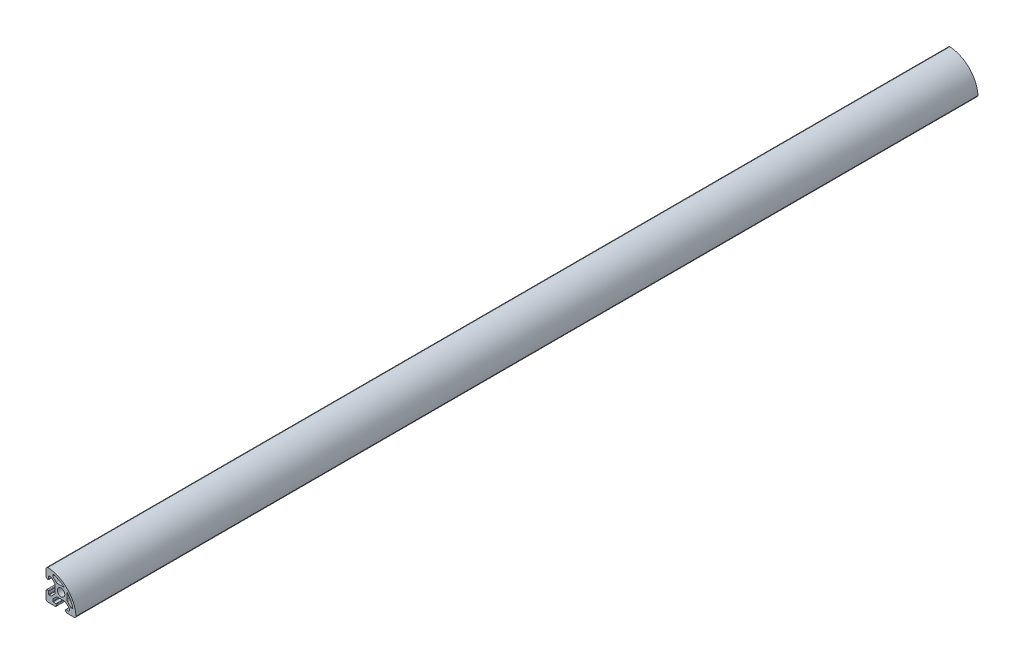
SolidWorks part; units mm, degrees
ref_plane "前视基准面" through (0, 0, 0) normal (0, 0, 1) x (1, 0, 0)
ref_plane "上视基准面" through (0, 0, 0) normal (0, 1, 0) x (1, 0, 0)
ref_plane "右视基准面" through (0, 0, 0) normal (1, 0, 0) x (0, 0, -1)
sketch "草图1" plane through (0, 0, 0) normal (0, 0, 1) x (1, 0, 0)
  line L14 (2.0848, 3.8649) -> (-2.342, 3.8649)
  line L15 (-3.4027, 4.3042) -> (-5.6233, 6.5249)
  line L16 (-5.6233, 6.5249) -> (-5.6233, 7.8649)
  line L22 (-10.1233, 8.4649) -> (-10.1233, 3.5649)
  line L23 (-10.1233, 3.5649) -> (-9.8233, 3.5649)
  line L24 (-9.6233, 3.3649) -> (-9.6233, 3.0649)
  line L25 (-9.6233, 3.0649) -> (-8.6233, 3.0649)
  line L26 (-8.3233, 3.3649) -> (-8.3233, 5.1649)
  line L27 (-8.0233, 5.4649) -> (-6.6833, 5.4649)
  line L28 (-6.6833, 5.4649) -> (-4.4627, 3.2442)
  line L29 (-4.0233, 2.1836) -> (-4.0233, -2.2538)
  line L30 (-4.4627, -3.3144) -> (-6.6833, -5.5351)
  line L31 (-6.6833, -5.5351) -> (-8.0233, -5.5351)
  line L32 (-8.3233, -5.2351) -> (-8.3233, -3.4351)
  line L33 (-8.6233, -3.1351) -> (-9.6233, -3.1351)
  line L34 (-9.6233, -3.1351) -> (-9.6233, -3.4351)
  line L35 (-9.8233, -3.6351) -> (-10.1233, -3.6351)
  line L36 (-10.1233, -3.6351) -> (-10.1233, -8.5351)
  line L37 (-8.6233, -10.0351) -> (-3.7233, -10.0351)
  line L38 (-3.7233, -10.0351) -> (-3.7233, -9.7351)
  line L39 (-3.5233, -9.5351) -> (-3.2233, -9.5351)
  line L40 (-3.2233, -9.5351) -> (-3.2233, -8.5351)
  line L41 (-3.5233, -8.2351) -> (-5.3233, -8.2351)
  line L42 (-5.6233, -7.9351) -> (-5.6233, -6.5951)
  line L43 (-5.6233, -6.5951) -> (-3.4027, -4.3744)
  line L44 (-2.342, -3.9351) -> (2.0953, -3.9351)
  line L45 (3.156, -4.3744) -> (5.3767, -6.5951)
  line L46 (5.3767, -6.5951) -> (5.3767, -7.9351)
  line L47 (5.0767, -8.2351) -> (3.2767, -8.2351)
  line L48 (2.9767, -8.5351) -> (2.9767, -9.5351)
  line L49 (2.9767, -9.5351) -> (3.2767, -9.5351)
  line L50 (3.4767, -9.7351) -> (3.4767, -10.0351)
  line L51 (3.4767, -10.0351) -> (8.3767, -10.0351)
  line L57 (7.7767, -5.5351) -> (6.4367, -5.5351)
  line L58 (6.4367, -5.5351) -> (4.216, -3.3144)
  line L59 (3.7767, -2.2538) -> (3.7767, 2.1836)
  circle A0 centre (-0.1233, -0.0351) radius 2.5
  arc A1 (7.8202, -5.5319) -> (3.7767, 2.1731) centre (-10.1233, -10.0351) ccw
  arc A2 (2.0848, 3.8649) -> (-5.6202, 7.9085) centre (-10.1233, -10.0351) ccw
  arc A9 (-3.4027, 4.3042) -> (-2.342, 3.8649) centre (-2.342, 5.3649) ccw
  arc A10 (-5.3233, 8.1649) -> (-5.6233, 7.8649) centre (-5.3233, 7.8649) ccw
  arc A13 (-8.6233, 9.9649) -> (-10.1233, 8.4649) centre (-8.6233, 8.4649) ccw
  arc A14 (-9.6233, 3.3649) -> (-9.8233, 3.5649) centre (-9.8233, 3.3649) ccw
  arc A15 (-8.6233, 3.0649) -> (-8.3233, 3.3649) centre (-8.6233, 3.3649) ccw
  arc A16 (-8.0233, 5.4649) -> (-8.3233, 5.1649) centre (-8.0233, 5.1649) ccw
  arc A17 (-4.0233, 2.1836) -> (-4.4627, 3.2442) centre (-5.5233, 2.1836) ccw
  arc A18 (-4.4627, -3.3144) -> (-4.0233, -2.2538) centre (-5.5233, -2.2538) ccw
  arc A19 (-8.3233, -5.2351) -> (-8.0233, -5.5351) centre (-8.0233, -5.2351) ccw
  arc A20 (-8.3233, -3.4351) -> (-8.6233, -3.1351) centre (-8.6233, -3.4351) ccw
  arc A21 (-9.8233, -3.6351) -> (-9.6233, -3.4351) centre (-9.8233, -3.4351) ccw
  arc A22 (-10.1233, -8.5351) -> (-8.6233, -10.0351) centre (-8.6233, -8.5351) ccw
  arc A23 (-3.5233, -9.5351) -> (-3.7233, -9.7351) centre (-3.5233, -9.7351) ccw
  arc A24 (-3.2233, -8.5351) -> (-3.5233, -8.2351) centre (-3.5233, -8.5351) ccw
  arc A25 (-5.6233, -7.9351) -> (-5.3233, -8.2351) centre (-5.3233, -7.9351) ccw
  arc A26 (-2.342, -3.9351) -> (-3.4027, -4.3744) centre (-2.342, -5.4351) ccw
  arc A27 (3.156, -4.3744) -> (2.0953, -3.9351) centre (2.0953, -5.4351) ccw
  arc A28 (5.0767, -8.2351) -> (5.3767, -7.9351) centre (5.0767, -7.9351) ccw
  arc A29 (3.2767, -8.2351) -> (2.9767, -8.5351) centre (3.2767, -8.5351) ccw
  arc A30 (3.4767, -9.7351) -> (3.2767, -9.5351) centre (3.2767, -9.7351) ccw
  arc A31 (8.3767, -10.0351) -> (9.8767, -8.5351) centre (8.3767, -8.5351) ccw
  arc A34 (7.7767, -5.5351) -> (7.8202, -5.5319) centre (7.7767, -5.2351) ccw
  arc A35 (3.7767, -2.2538) -> (4.216, -3.3144) centre (5.2767, -2.2538) ccw
  arc A37 (9.8419, -8.8562) -> (-8.9445, 9.9301) centre (-10.1233, -10.0351) ccw
extrude "凸台-拉伸1" add sketch "草图1" along normal blind 600 contours A31 A37 A13 L22 L23 A14 L24 L25 A15 L26 A16 L27 L28 A17 L29 A18 L30 L31 A19 L32 A20 L33 L34 A21 L35 L36 A22 L37 L38 A23 L39 L40 A24 L41 A25 L42 L43 A26 L44 A27 L45 L46 A28 L47 A29 L48 L49 A30 L50 L51
